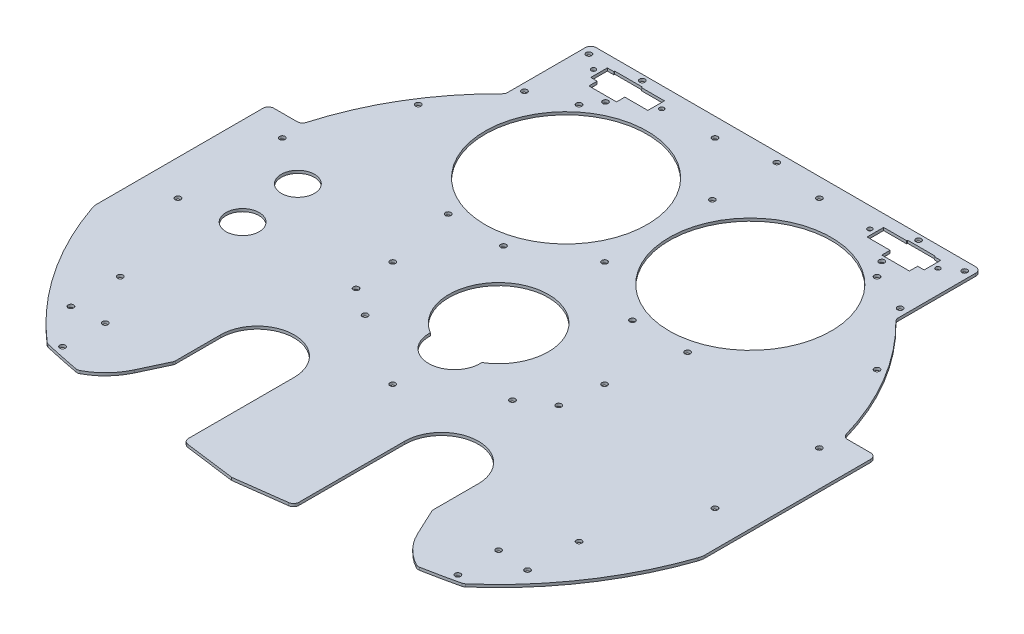
SolidWorks part; units mm, degrees
material "3.0205 (EN-AW 1200)"
ref_plane "Plan de face" through (0, 0, 0) normal (0, 0, 1) x (1, 0, 0)
ref_plane "Plan de dessus" through (0, 0, 0) normal (0, 1, 0) x (1, 0, 0)
ref_plane "Plan de droite" through (0, 0, 0) normal (1, 0, 0) x (0, 0, -1)
sketch "Esquisse1" plane through (0, 0, 0) normal (0, 1, 0) x (1, 0, 0)
  line L2 (0, 0) -> (165, 0) construction
  line L4 (165, -54.557) -> (165, 55.2417)
  line L5 (-165, 55.2417) -> (-104.5177, 160)
  line L6 (-165, -54.557) -> (-165, 55.2417)
  line L9 (0, 160) -> (0, 0) construction
  line L12 (-104.5177, 160) -> (104.5177, 160)
  line L13 (165, 55.2417) -> (104.5177, 160)
  arc A0 (-165, -54.557) -> (-112.9493, -132.0754) centre (0, 0) ccw
  circle A1 centre (158.5, 53.5) radius 6.5 construction
  circle A2 centre (-158.5, 53.5) radius 6.5 construction
  circle A3 centre (158.5, -53.5) radius 6.5 construction
  circle A4 centre (-158.5, -53.5) radius 6.5 construction
  arc A5 (-112.9493, -132.0754) -> (112.9493, -132.0754) centre (0, 355) ccw
  arc A6 (112.9493, -132.0754) -> (165, -54.557) centre (0, 0) ccw
  point P21 (0, -145)
  dimension "D2" = 145
  dimension "D13" = 225.8987
  dimension "D16" = 500
  dimension "D9" = 13
  dimension "D12" = 317
  dimension "D15" = 107
  dimension "D4" = 60
  dimension "D5" = 209.0355
  dimension "D6" = 330
  dimension "D7" = 120.9645
  dimension "D8" = 109.7986
  dimension "D10" = 93.3723
  dimension "D11" = 160
extrude "Boss.-Extru.1" add sketch "Esquisse1" along normal blind 1.5
sketch "Esquisse2" plane through (0, 1.5, 0) normal (0, 1, 0) x (1, 0, 0)
  line L1 (0, 0) -> (120, 0) construction
  line L2 (0, 0) -> (0, 50) construction
  circle A0 centre (120, 50) radius 2.5 construction
  circle A1 centre (-120, 50) radius 2.5 construction
  circle A2 centre (-120, -50) radius 2.5 construction
  circle A3 centre (120, -50) radius 2.5 construction
  arc A4 (13.9713, -23.1042) -> (-13.9713, -23.1042) centre (0, 0) ccw
  arc A5 (-13.9713, -23.1042) -> (13.9713, -23.1042) centre (0, -24) ccw
  circle A6 centre (0, 57.5) radius 1.5
  circle A7 centre (57.5, 0) radius 1.5
  circle A8 centre (-57.5, 0) radius 1.5
  circle A9 centre (0, -57.5) radius 1.5
  circle A10 centre (0, 0) radius 57.5 construction
  dimension "D1" = 100
  dimension "D2" = 240
  dimension "D3" = 5
  dimension "D4" = 24
  dimension "D5" = 54
  dimension "D8" = 115
  dimension "D6" = 14
  dimension "D7" = 3
extrude "Enlèv. mat.-Extru.1" cut sketch "Esquisse2" against normal blind 10
sketch "Esquisse3" plane through (0, 1.5, 0) normal (0, 1, 0) x (1, 0, 0)
  line L0 (-50, 86.6025) -> (0, 0) construction
  line L1 (0, 0) -> (50, 86.6025) construction
  line L2 (50, 86.6025) -> (-50, 86.6025) construction
  line L3 (0, 0) -> (0, -145) construction
  line L4 (0, 0) -> (50, -86.6025) construction
  line L5 (-75, 149.5) -> (-75, 140.5) construction
  line L6 (-90.5, 149.5) -> (-59.5, 149.5)
  line L7 (70, -145) -> (70, -81)
  line L8 (-30, -145) -> (-70, -145)
  line L9 (-30, -145) -> (-30, -81)
  line L10 (-30, -81) -> (-70, -81) construction
  line L11 (-70, -145) -> (-70, -81)
  line L12 (30, -81) -> (70, -81) construction
  line L13 (30, -145) -> (30, -81)
  line L14 (30, -145) -> (70, -145)
  line L15 (-90.5, 149.5) -> (-90.5, 140.5)
  line L16 (-90.5, 140.5) -> (-59.5, 140.5)
  line L17 (-59.5, 149.5) -> (-59.5, 140.5)
  line L18 (59.5, 149.5) -> (59.5, 140.5)
  line L19 (90.5, 140.5) -> (59.5, 140.5)
  line L20 (90.5, 149.5) -> (90.5, 140.5)
  line L21 (90.5, 149.5) -> (59.5, 149.5)
  line L22 (104.5177, 160) -> (-104.5177, 160) construction
  circle A0 centre (-50, 86.6025) radius 44
  circle A1 centre (50, 86.6025) radius 44
  arc A2 (-112.9493, -132.0754) -> (112.9493, -132.0754) centre (0, 355) ccw construction
  arc A3 (70, -81) -> (30, -81) centre (50, -81) ccw
  arc A4 (-70, -81) -> (-30, -81) centre (-50, -81) cw
  circle A5 centre (-93.5, 145) radius 1.25
  circle A6 centre (-56.5, 145) radius 1.25
  circle A7 centre (56.5, 145) radius 1.25
  circle A8 centre (93.5, 145) radius 1.25
  point P39 (-90.5, 145)
  dimension "D2" = 100
  dimension "D3" = 88
  dimension "D6" = 86.6025
  dimension "D7" = 31
  dimension "D9" = 2.5
  dimension "D10" = 37
  dimension "D11" = 15
  dimension "D12" = 150
  dimension "D1" = 100
  dimension "D4" = 81
  dimension "D5" = 40
  dimension "D8" = 9
extrude "Enlèv. mat.-Extru.2" cut sketch "Esquisse3" against normal up to next
sketch "Esquisse4" plane through (0, 1.5, 0) normal (0, 1, 0) x (1, 0, 0)
  line L0 (0, 0) -> (0, -145) construction
  line L1 (-70, -105.9976) -> (-76.865, -120.7195)
  line L2 (-70, -140.0758) -> (-107.0437, -139.772)
  line L3 (-70, -105.9976) -> (-70, -140.0758)
  line L4 (70, -105.9976) -> (70, -140.0758)
  line L5 (0, 0) -> (-106.7731, -106.7731) construction
  line L6 (-70, -81) -> (-70, -140.0758) construction
  line L7 (70, -140.0758) -> (107.0437, -139.772)
  line L8 (70, -105.9976) -> (76.865, -120.7195)
  line L10 (-30, -145) -> (30, -145)
  line L11 (-30, -145) -> (-30, -141.0123)
  line L12 (-30, -141.0123) -> (0, -144.9619)
  line L15 (-106.7731, -106.7731) -> (-30, -116.8805) construction
  line L16 (30, -145) -> (30, -141.0123)
  line L17 (30, -141.0123) -> (0, -144.9619)
  line L18 (-30, -144.0992) -> (-30, -81) construction
  line L19 (0, 0) -> (-3.704, -141.4484) construction
  circle A0 centre (-106.7731, -106.7731) radius 1.5
  arc A1 (107.0437, -139.772) -> (76.865, -120.7195) centre (106.7731, -106.7731) cw
  arc A2 (-30, -144.0992) -> (30, -144.0992) centre (0, 355) ccw construction
  circle A3 centre (-106.7731, -106.7731) radius 36.7731 construction
  circle A4 centre (106.7731, -106.7731) radius 1.5
  circle A5 centre (107.3031, -129.4378) radius 1.5
  arc A6 (-107.0437, -139.772) -> (-76.865, -120.7195) centre (-106.7731, -106.7731) ccw
  circle A7 centre (123.9537, -108.2776) radius 1.5
  circle A8 centre (-123.9537, -108.2776) radius 1.5
  circle A9 centre (-107.3031, -129.4378) radius 1.5
  circle A10 centre (107.3031, -129.4378) radius 1.2 construction
  circle A11 centre (123.9537, -108.2776) radius 1.2 construction
  point P30 (-3.704, -141.4484)
  dimension "D1" = 97.4
  dimension "D2" = 151
  dimension "D3" = 3
  dimension "D5" = 25
  dimension "D6" = 33
  dimension "D7" = 52.5
  dimension "D4" = 45
  dimension "D8" = 1.5
  dimension "D9" = 3
  dimension "D10" = 23.9254
extrude "Enlèv. mat.-Extru.3" cut sketch "Esquisse4" against normal up to next
fillet "Congé1" radius 3 8 edges at (-70, 0.75, 105.9976) (70, 0.75, 105.9976) (92.2658, 0.75, 136.4133) (30, 0.75, 141.0123) (-30, 0.75, 141.0123) (-92.2658, 0.75, 136.4133) (-112.9493, 0.75, 132.0754) (112.9493, 0.75, 132.0754)
sketch "Esquisse5" plane through (0, 1.5, 0) normal (0, 1, 0) x (1, 0, 0)
  circle A0 centre (-120, 11) radius 9
  circle A1 centre (-117, -22) radius 9
  dimension "D1" = 11
  dimension "D2" = 18
  dimension "D3" = 120
  dimension "D4" = 22
  dimension "D5" = 18
  dimension "D6" = 117
extrude "Enlèv. mat.-Extru.4" cut sketch "Esquisse5" against normal through all
sketch "Esquisse6" plane through (0, 1.5, 0) normal (0, 1, 0) x (1, 0, 0)
  line L0 (0, 0) -> (-124.5426, -80.8789) construction
  line L1 (0, 0) -> (-145.7716, -28.3351) construction
  line L2 (0, 0) -> (-165, 0) construction
  line L3 (-165, 55.2417) -> (-165, -54.557) construction
  circle A0 centre (-124.5426, -80.8789) radius 1.5
  circle A1 centre (-145.7716, -28.3351) radius 1.5
  circle A2 centre (-145.7716, 28.3351) radius 1.5
  circle A3 centre (-124.5426, 80.8789) radius 1.5
  dimension "D1" = 4
  dimension "D5" = 3
  dimension "D2" = 22
  dimension "D3" = 11
  dimension "D4" = 148.5
extrude "Enlèv. mat.-Extru.5" cut sketch "Esquisse6" against normal through all
pattern_circular "Répétition circulaire1" count 3 every 90 about axis through (0, 0, 0) along (0, 1, 0) of "Enlèv. mat.-Extru.5"
sketch "Esquisse7" plane through (0, 1.5, 0) normal (0, 1, 0) x (1, 0, 0)
  line L0 (-165, 55.2417) -> (-165, -54.557) construction
  line L1 (-104.5177, 160) -> (-165, 55.2417) construction
  line L2 (104.5177, 160) -> (-104.5177, 160) construction
  line L3 (165, 55.2417) -> (104.5177, 160) construction
  line L4 (165, -54.557) -> (165, 55.2417) construction
  line L5 (-165, 55.2417) -> (-165, 40)
  line L6 (-104.5177, 160) -> (-165, 55.2417)
  line L7 (104.5177, 160) -> (-104.5177, 160)
  line L8 (165, 55.2417) -> (104.5177, 160)
  line L9 (165, 40) -> (165, 55.2417)
  line L10 (0, 0) -> (0, -144.9619) construction
  line L11 (106, 109.6369) -> (106, 156)
  line L12 (-106, 156) -> (106, 156)
  line L13 (-106, 156) -> (-106, 109.6369)
  line L14 (27.3916, -141.3557) -> (0, -144.9619) construction
  line L20 (147.1606, 40) -> (165, 40)
  line L21 (-147.1606, 40) -> (-165, 40)
  arc A0 (147.1606, 40) -> (106, 109.6369) centre (0, 0) ccw
  arc A1 (-106, 109.6369) -> (-147.1606, 40) centre (0, 0) ccw
  circle A2 centre (-65, 37.6) radius 1.5
  circle A3 centre (-35, 37.6) radius 1.5
  circle A4 centre (-55, -22.4) radius 1.5
  circle A7 centre (55, -22.4) radius 1.5
  circle A8 centre (35, 37.6) radius 1.5
  circle A9 centre (65, 37.6) radius 1.5
  point P10 (0, 156)
  dimension "D3" = 152.5
  dimension "D5" = 30
  dimension "D6" = 3
  dimension "D7" = 60
  dimension "D8" = 10
  dimension "D1" = 40
  dimension "D4" = 4
  dimension "D2" = 212
  dimension "D9" = 55
  dimension "D10" = 22.4
extrude "Enlèv. mat.-Extru.6" cut sketch "Esquisse7" against normal through all
fillet "Congé2" radius 10 2 edges at (165, 0.75, 54.557) (-165, 0.75, 54.557)
fillet "Congé3" radius 3 8 edges at (165, 0.75, -40) (-165, 0.75, -40) (-147.1606, 0.75, -40) (-106, 0.75, -109.6369) (-106, 0.75, -156) (106, 0.75, -156) (106, 0.75, -109.6369) (147.1606, 0.75, -40)
sketch "Esquisse8" plane through (0, 1.5, 0) normal (0, 1, 0) x (1, 0, 0)
  line L1 (-87, 150) -> (-72, 150)
  line L2 (-87, 150) -> (-87, 136)
  line L3 (-87, 136) -> (-72, 136)
  line L4 (-72, 150) -> (-72, 136)
  line L5 (-103, 156) -> (103, 156) construction
  line L6 (0, 156) -> (0, 0) construction
  line L7 (87, 136) -> (72, 136)
  line L8 (87, 150) -> (87, 136)
  line L9 (87, 150) -> (72, 150)
  line L10 (72, 150) -> (72, 136)
  circle A0 centre (75, 133) radius 1.5
  circle A1 centre (-75, 153) radius 1.5
  circle A2 centre (75, 153) radius 1.5
  circle A3 centre (-75, 133) radius 1.5
  dimension "D1" = 12
  dimension "D5" = 23
  dimension "D6" = 3
  dimension "D7" = 75
  dimension "D8" = 3
  dimension "D2" = 3
  dimension "D3" = 14
  dimension "D4" = 3
extrude "Enlèv. mat.-Extru.7" cut sketch "Esquisse8" against normal through all
sketch "Esquisse9" plane through (0, 1.5, 0) normal (0, 1, 0) x (1, 0, 0)
  line L0 (-103, 156) -> (103, 156) construction
  circle A0 centre (-102, 151) radius 1.5
  circle A1 centre (0, 151) radius 1.5
  circle A2 centre (102, 151) radius 1.5
  circle A3 centre (0, 116) radius 1.5
  circle A4 centre (102, 116) radius 1.5
  circle A5 centre (-102, 116) radius 1.5
  dimension "D1" = 3
  dimension "D3" = 3
  dimension "D4" = 102
  dimension "D5" = 35
  dimension "D6" = 5
  dimension "D2" = 2
extrude "Enlèv. mat.-Extru.8" cut sketch "Esquisse9" against normal blind 3
sketch "Esquisse10" plane through (0, 1.5, 0) normal (0, 1, 0) x (1, 0, 0)
  line L0 (0, 0) -> (-40, -32.5) construction
  line L2 (0, -57.5) -> (0, 0) construction
  circle A0 centre (-40, -32.5) radius 1.5
  circle A1 centre (40, -32.5) radius 1.5
  point P7 (0, -22.5)
  dimension "D1" = 80
  dimension "D2" = 3
  dimension "D3" = 22.5
  dimension "D4" = 10
  dimension "D5" = 51.5388
  dimension "D6" = 57.5
extrude "Enlèv. mat.-Extru.9" cut sketch "Esquisse10" against normal through all
sketch "Esquisse11" plane through (0, 1.5, 0) normal (0, 1, 0) x (1, 0, 0)
  circle A0 centre (0, 0) radius 60
  dimension "D1" = 120
